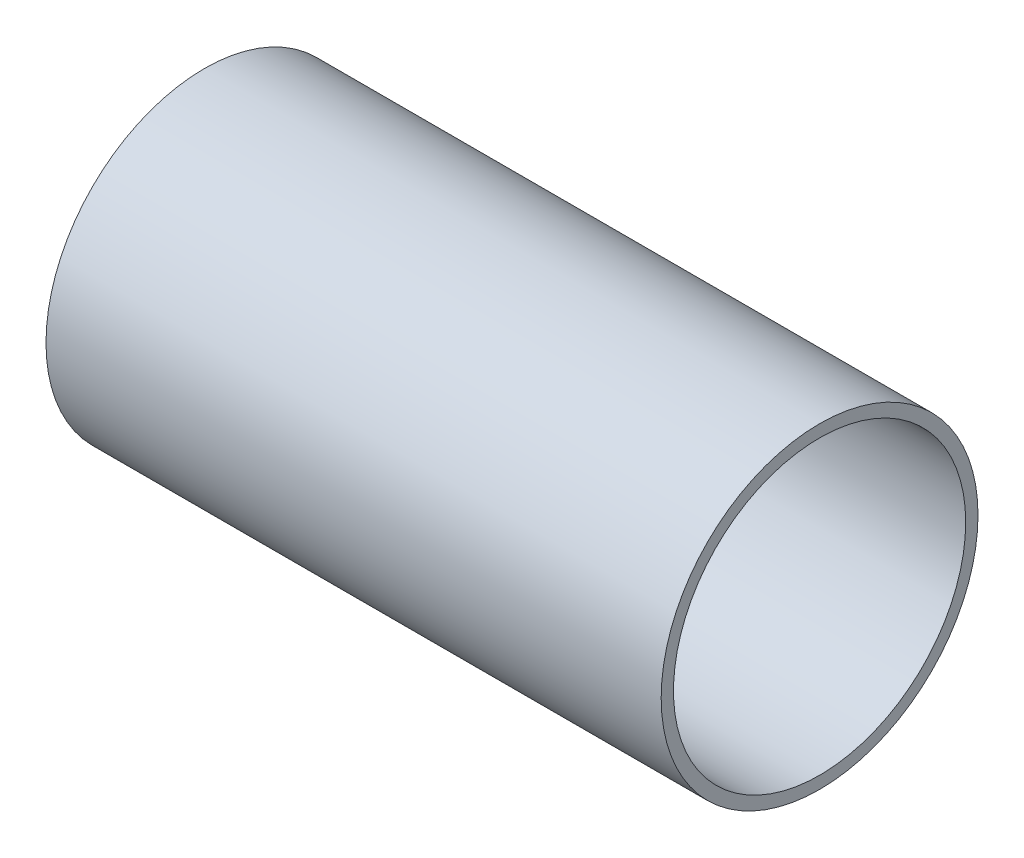
SolidWorks part; units mm, degrees
ref_plane "Plan de face" through (0, 0, 0) normal (0, 0, 1) x (1, 0, 0)
ref_plane "Plan de dessus" through (0, 0, 0) normal (0, 1, 0) x (1, 0, 0)
ref_plane "Plan de droite" through (0, 0, 0) normal (1, 0, 0) x (0, 0, -1)
other "Centre de masse"
sketch "Esquisse1" plane through (0, 0, 0) normal (1, 0, 0) x (0, 0, -1)
  circle A0 centre (0, 0) radius 47.5
  circle A1 centre (0, 0) radius 51.5
extrude "Boss.-Extru.1" add sketch "Esquisse1" along normal blind 200
